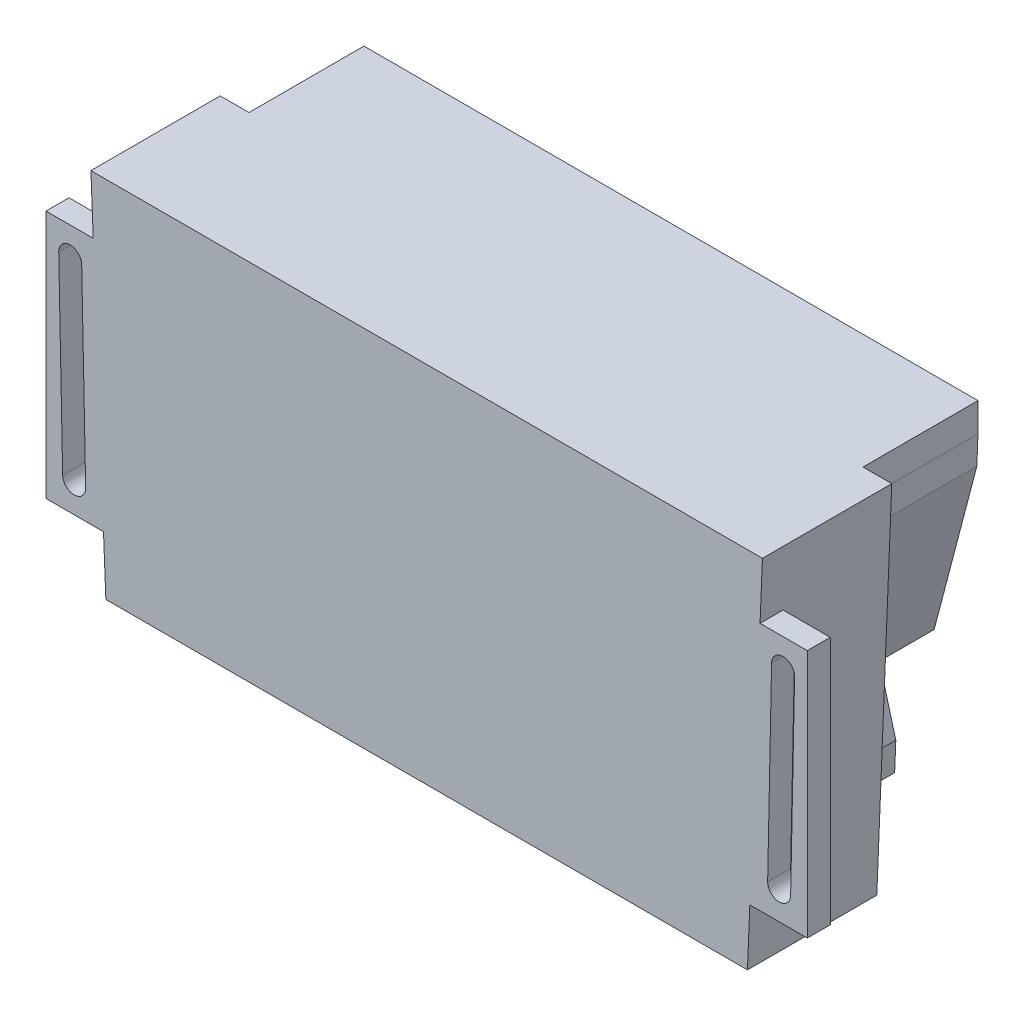
SolidWorks part; units mm, degrees
ref_plane "Front Plane" through (0, 0, 0) normal (0, 0, 1) x (1, 0, 0)
ref_plane "Top Plane" through (0, 0, 0) normal (0, 1, 0) x (1, 0, 0)
ref_plane "Right Plane" through (0, 0, 0) normal (1, 0, 0) x (0, 0, -1)
sketch "Sketch1" plane through (0, 0, 0) normal (0, 0, 1) x (1, 0, 0)
  line L0 (0, 0) -> (5.2, 0)
  line L1 (5.2, 0) -> (7.6, 58.3)
  line L2 (7.6, 58.3) -> (-2.4, 58.3)
  line L3 (-2.4, 58.3) -> (0, 0)
  line L4 (2.6, 58.3) -> (2.6, 0) construction
  line L5 (-1.0292, 25) -> (6.2292, 25)
  line L10 (9.7, 58.3) -> (12.1, 0)
  line L15 (12.1, 0) -> (17.3, 0)
  line L20 (17.3, 0) -> (19.7, 58.3)
  line L25 (19.7, 58.3) -> (9.7, 58.3)
  line L30 (12.0708, 25) -> (19.4942, 53.3)
  line L35 (12.0708, 25) -> (17.5058, 5)
  line L40 (11.0708, 25) -> (18.3292, 25)
  line L45 (21.8, 58.3) -> (24.2, 0)
  line L46 (-0.0292, 25) -> (5.4058, 5)
  line L47 (-0.0292, 25) -> (7.3942, 53.3)
  line L48 (24.2, 0) -> (29.4, 0)
  line L49 (29.4, 0) -> (31.8, 58.3)
  line L50 (31.8, 58.3) -> (21.8, 58.3)
  line L51 (24.1708, 25) -> (31.5942, 53.3)
  line L52 (24.1708, 25) -> (29.6058, 5)
  line L53 (23.1708, 25) -> (30.4292, 25)
  line L54 (33.9, 58.3) -> (36.3, 0)
  line L55 (36.3, 0) -> (41.5, 0)
  line L56 (41.5, 0) -> (43.9, 58.3)
  line L57 (43.9, 58.3) -> (33.9, 58.3)
  line L58 (36.2708, 25) -> (43.6942, 53.3)
  line L59 (36.2708, 25) -> (41.7058, 5)
  line L60 (35.2708, 25) -> (42.5292, 25)
  line L61 (46, 58.3) -> (48.4, 0)
  line L62 (48.4, 0) -> (53.6, 0)
  line L63 (53.6, 0) -> (56, 58.3)
  line L64 (56, 58.3) -> (46, 58.3)
  line L65 (48.3708, 25) -> (55.7942, 53.3)
  line L66 (48.3708, 25) -> (53.8058, 5)
  line L67 (47.3708, 25) -> (54.6292, 25)
  line L68 (58.1, 58.3) -> (60.5, 0)
  line L69 (60.5, 0) -> (65.7, 0)
  line L70 (65.7, 0) -> (68.1, 58.3)
  line L71 (68.1, 58.3) -> (58.1, 58.3)
  line L72 (60.4708, 25) -> (67.8942, 53.3)
  line L73 (60.4708, 25) -> (65.9058, 5)
  line L74 (59.4708, 25) -> (66.7292, 25)
  line L75 (70.2, 58.3) -> (72.6, 0)
  line L76 (72.6, 0) -> (77.8, 0)
  line L77 (77.8, 0) -> (80.2, 58.3)
  line L78 (80.2, 58.3) -> (70.2, 58.3)
  line L79 (72.5708, 25) -> (79.9942, 53.3)
  line L80 (72.5708, 25) -> (78.0058, 5)
  line L81 (71.5708, 25) -> (78.8292, 25)
  line L82 (82.3, 58.3) -> (84.7, 0)
  line L83 (84.7, 0) -> (89.9, 0)
  line L84 (89.9, 0) -> (92.3, 58.3)
  line L85 (92.3, 58.3) -> (82.3, 58.3)
  line L86 (84.6708, 25) -> (92.0942, 53.3)
  line L87 (84.6708, 25) -> (90.1058, 5)
  line L88 (83.6708, 25) -> (90.9292, 25)
  line L89 (94.4, 58.3) -> (96.8, 0)
  line L90 (96.8, 0) -> (102, 0)
  line L91 (102, 0) -> (104.4, 58.3)
  line L92 (104.4, 58.3) -> (94.4, 58.3)
  line L93 (96.7708, 25) -> (104.1942, 53.3)
  line L94 (96.7708, 25) -> (102.2058, 5)
  line L95 (95.7708, 25) -> (103.0292, 25)
  dimension "D1" = 5.2
  dimension "D2" = 10
  dimension "D3" = 58.3
  dimension "D4" = 25
  dimension "D6" = 2.1
  dimension "D7" = 5
  dimension "D8" = 5
  dimension "D9" = 1
  dimension "D5" = 9
extrude "Boss-Extrude1" add sketch "Sketch1" along normal blind 20 contours L4 L2 L3 L5 L47 | L2 L4 L47 L1 | L10 L40 L30 L20 L25 | L45 L53 L51 L49 L50 | L54 L60 L58 L56 L57 | L61 L67 L65 L63 L64 | L68 L74 L72 L70 L71 | L75 L81 L79 L77 L78 | L82 L88 L86 L84 L85 | L89 L95 L93 L91 L92 | L88 L82 L83 L84 L87 | L81 L75 L76 L77 L80 | L74 L68 L69 L70 L73 | L67 L61 L62 L63 L66 | L60 L54 L55 L56 L59 | L53 L45 L48 L49 L52 | L40 L10 L15 L20 L35
sketch "Sketch2" plane through (0, 58.3, 0) normal (0, 1, 0) x (1, 0, 0)
  line L0 (104.4, -20) -> (94.4, -20) construction
  line L1 (104.4, 0) -> (-2.4, 0)
  line L2 (104.4, 0) -> (104.4, -20)
  line L3 (104.4, -20) -> (-2.4, -20)
  line L4 (-2.4, 0) -> (-2.4, -20)
extrude "Boss-Extrude2" add sketch "Sketch2" along normal blind 5
sketch "Sketch3" plane through (0, 0, 20) normal (0, 0, 1) x (1, 0, 0)
  line L0 (109.4042, 63.3) -> (107.0042, 5)
  line L1 (107.0042, 5) -> (-5, 5)
  line L2 (-5, 5) -> (-7.4, 63.3)
  line L3 (-7.4, 63.3) -> (109.4042, 63.3)
  line L6 (-2.4, 63.3) -> (104.4, 63.3) construction
  line L7 (-2.4, 58.3) -> (-1.0292, 25) construction
  line L9 (104.1942, 53.3) -> (104.4, 58.3) construction
  dimension "D1" = 5
  dimension "D2" = 5
  dimension "D3" = 5.0042
extrude "Boss-Extrude3" add sketch "Sketch3" along normal blind 12.5
sketch "Sketch4" plane through (0, 0, 32.5) normal (0, 0, 1) x (1, 0, 0)
  line L0 (107.0042, 5) -> (-5, 5)
  line L1 (-5, 5) -> (-5.2058, 10)
  line L2 (-7.4, 63.3) -> (-5, 5) construction
  line L3 (-5.2058, 10) -> (107.2101, 10)
  line L4 (107.0042, 5) -> (109.4042, 63.3) construction
  line L5 (107.2101, 10) -> (107.0042, 5)
  line L6 (107.2101, 10) -> (109.4042, 63.3)
  line L7 (109.4042, 63.3) -> (106.4042, 63.3)
  line L8 (109.4042, 63.3) -> (-7.4, 63.3) construction
  line L9 (106.4042, 63.3) -> (106.4042, 10)
  line L10 (106.4042, 10) -> (107.2101, 10)
  line L11 (-5.2058, 10) -> (-7.4, 63.3)
  line L12 (-7.4, 63.3) -> (-4.4, 63.3)
  line L13 (-4.4, 63.3) -> (-4.4, 10)
  line L14 (-4.4, 10) -> (-5.2058, 10)
  line L15 (-7.4, 63.3) -> (-5, 5) construction
  line L16 (5.6, 10) -> (96.4042, 10)
  line L17 (5.6, 10) -> (5.6, 63.3)
  line L18 (5.6, 63.3) -> (96.4042, 63.3)
  line L19 (96.4042, 10) -> (96.4042, 63.3)
  point P25 (51.0021, 10)
  point P26 (51.0021, 63.3)
  line M13 (109.4042, 63.3) -> (-7.4, 63.3)
  line M14 (-7.4, 63.3) -> (-5, 5)
  line M15 (-5, 5) -> (107.0042, 5)
  line M16 (107.0042, 5) -> (109.4042, 63.3)
  dimension "D1" = 5
  dimension "D2" = 3
  dimension "D3" = 10
extrude "Boss-Extrude4" add sketch "Sketch4" along normal blind 10 contours L3 M14 M15 M16 | L13 L3 M13 M14 | L6 L7 L9 L10 | L17 L16 L19 L18
sketch "Sketch7" plane through (0, 10, 0) normal (0, 1, 0) x (1, 0, 0)
  line L0 (101.4042, -42.5) -> (101.4042, -32.5) construction
  line L1 (96.4042, -42.5) -> (106.4042, -42.5) construction
  line L2 (96.4042, -32.5) -> (106.4042, -32.5) construction
  line L3 (0.6, -42.5) -> (0.6, -32.5) construction
  line L4 (-4.4, -42.5) -> (5.6, -42.5) construction
  line L5 (-4.4, -32.5) -> (5.6, -32.5) construction
  circle A0 centre (101.4042, -29.5) radius 2.9
  circle A1 centre (0.6, -29.5) radius 2.9
  point P16 (0, 0)
  point P17 (101.4042, -32.5)
  point P18 (101.4042, -32.5)
  dimension "D1" = 5.8
  dimension "D2" = 3
extrude "Cut-Extrude3" cut sketch "Sketch7" against normal through all
sketch "Sketch8" plane through (0, 10, 0) normal (0, 1, 0) x (1, 0, 0)
  line L4 (96.4042, -42.5) -> (106.4042, -42.5)
  line L5 (106.4042, -42.5) -> (106.4042, -32.5)
  line L6 (106.4042, -32.5) -> (96.4042, -32.5)
  line L7 (96.4042, -32.5) -> (96.4042, -42.5)
  line L8 (96.4042, -42.5) -> (106.4042, -42.5)
  line L9 (106.4042, -42.5) -> (106.4042, -32.5)
  line L10 (106.4042, -32.5) -> (96.4042, -32.5)
  line L11 (96.4042, -32.5) -> (96.4042, -42.5)
  line L12 (-4.4, -42.5) -> (5.6, -42.5)
  line L13 (5.6, -42.5) -> (5.6, -32.5)
  line L14 (5.6, -32.5) -> (-4.4, -32.5)
  line L15 (-4.4, -32.5) -> (-4.4, -42.5)
  line L16 (-4.4, -42.5) -> (5.6, -42.5)
  line L17 (5.6, -42.5) -> (5.6, -32.5)
  line L18 (5.6, -32.5) -> (-4.4, -32.5)
  line L19 (-4.4, -32.5) -> (-4.4, -42.5)
  circle A0 centre (101.4042, -29.5) radius 2.9 construction
  circle A1 centre (101.4042, -29.5) radius 2.9
  circle A2 centre (0.6, -29.5) radius 2.9 construction
  circle A3 centre (0.6, -29.5) radius 2.9
  dimension "D1" = 0
  dimension "D2" = 0
extrude "Boss-Extrude6" add sketch "Sketch8" along normal up to surface (53.3 mm away) up to face at (51.0016, 63.3, 29.0625)
sketch "Sketch10" plane through (0, 0, 20) normal (0, 0, 1) x (1, 0, 0)
  line L1 (107.0042, 5) -> (109.4042, 63.3) construction
  line L2 (84.7, 0) -> (89.9, 0) construction
  line L23 (-4.7942, 0) -> (106.7984, 0)
  line L24 (-4.7942, 0) -> (-5, 5)
  line L25 (-5, 5) -> (107.0042, 5)
  line L26 (106.7984, 0) -> (107.0042, 5)
  line L27 (-5, 5) -> (11.8942, 5) construction
  line L28 (-7.4, 63.3) -> (-5, 5) construction
extrude "Boss-Extrude7" add sketch "Sketch10" along normal up to surface (22.5 mm away) up to face at (51.0021, 34.15, 42.5)
sketch "Sketch12" plane through (0, 5, 0) normal (0, 1, 0) x (1, 0, 0)
  circle A1 centre (101.4042, -29.5) radius 2.9
  circle A2 centre (101.4042, -29.5) radius 2.9
  circle A3 centre (0.6, -29.5) radius 2.9
  circle A4 centre (0.6, -29.5) radius 2.9
  dimension "D1" = 0
  dimension "D2" = 0
extrude "Cut-Extrude6" cut sketch "Sketch12" against normal through all
sketch "Sketch13" plane through (0, 0, 42.5) normal (0, 0, 1) x (1, 0, 0)
  line L0 (112.2101, 10) -> (113.1013, 53.3) construction
  line L5 (108.9926, 53.3) -> (107.2101, 10)
  line L6 (106.7984, 0) -> (109.4042, 63.3) construction
  line L9 (107.2101, 10) -> (117.2101, 10)
  line L10 (117.2101, 10) -> (117.2101, 53.3)
  line L13 (117.2101, 53.3) -> (108.9926, 53.3)
  line L14 (112.313, 15) -> (112.9984, 48.3) construction
  line L15 (110.3134, 15.0412) -> (110.9988, 48.3412)
  line L16 (114.3126, 14.9588) -> (114.998, 48.2588)
  line L17 (51.0021, 63.3) -> (51.0021, 0) construction
  line L18 (109.4042, 63.3) -> (-7.4, 63.3) construction
  line L19 (-4.7942, 0) -> (106.7984, 0) construction
  line L20 (-10.3087, 15) -> (-10.9942, 48.3) construction
  line L21 (-8.3092, 15.0412) -> (-8.9946, 48.3412)
  line L22 (-12.3083, 14.9588) -> (-12.9937, 48.2588)
  line L23 (-15.2058, 10) -> (-15.2058, 53.3)
  line L24 (-5.2058, 10) -> (-15.2058, 10)
  line L25 (-6.9883, 53.3) -> (-5.2058, 10)
  line L26 (-15.2058, 53.3) -> (-6.9883, 53.3)
  arc A0 (110.3134, 15.0412) -> (114.3126, 14.9588) centre (112.313, 15) ccw
  arc A1 (114.998, 48.2588) -> (110.9988, 48.3412) centre (112.9984, 48.3) ccw
  arc A2 (-8.3092, 15.0412) -> (-12.3083, 14.9588) centre (-10.3087, 15) cw
  arc A3 (-12.9937, 48.2588) -> (-8.9946, 48.3412) centre (-10.9942, 48.3) cw
  point P12 (112.6557, 31.65)
  point P25 (-10.6515, 31.65)
  dimension "D1" = 10
  dimension "D2" = 10
  dimension "D3" = 10
  dimension "D4" = 5
  dimension "D5" = 5
  dimension "D6" = 4
extrude "Boss-Extrude8" add sketch "Sketch13" against normal blind 4
